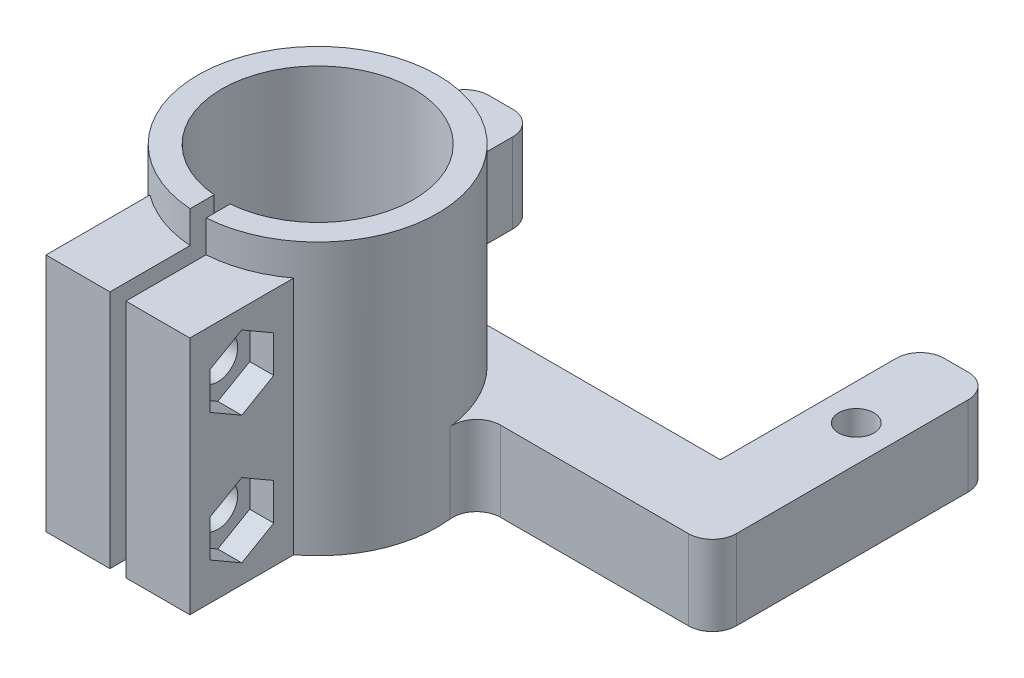
SolidWorks part; units mm, degrees
ref_plane "前视基准面" through (0, 0, 0) normal (0, 0, 1) x (1, 0, 0)
ref_plane "上视基准面" through (0, 0, 0) normal (0, 1, 0) x (1, 0, 0)
ref_plane "右视基准面" through (0, 0, 0) normal (1, 0, 0) x (0, 0, -1)
sketch "草图1" plane through (0, 0, 0) normal (0, 1, 0) x (1, 0, 0)
  circle A0 centre (0, 0) radius 6
  circle A1 centre (0, 0) radius 7.5
  dimension "D1" = 12
  dimension "D2" = 15
extrude "凸台-拉伸1" add sketch "草图1" along normal blind 17
ref_plane "基准面1" through (0, 0, 7.5) normal (0, 0, 1) x (1, 0, 0)
sketch "草图2" plane through (0, 0, 7.5) normal (0, 0, 1) x (1, 0, 0)
  line L0 (0, 0) -> (0, 17) construction
  line L1 (6, 17) -> (-6, 17) construction
  line L2 (-7.5, 0) -> (7.5, 0) construction
  line L3 (-0.5, 17) -> (0.5, 17)
  line L4 (-0.5, 17) -> (-0.5, 0)
  line L5 (-0.5, 0) -> (0.5, 0)
  line L6 (0.5, 17) -> (0.5, 0)
  line L7 (-0.5, 17) -> (0.5, 0) construction
  line L8 (-0.5, 0) -> (0.5, 17) construction
  point P5 (0, 8.5)
  dimension "D1" = 1
extrude "切除-拉伸1" cut sketch "草图2" against normal up to next
sketch "草图3" plane through (0, 0, 7.5) normal (0, 0, 1) x (1, 0, 0)
  line L0 (-7.5, 0) -> (7.5, 0) construction
  line L1 (-0.5, 17) -> (-4.5, 17)
  line L2 (-0.5, 17) -> (-0.5, 0)
  line L3 (-0.5, 0) -> (-4.5, 0)
  line L4 (-4.5, 17) -> (-4.5, 0)
  line L6 (0.5, 17) -> (4.5, 17)
  line L7 (0.5, 17) -> (0.5, 0)
  line L8 (0.5, 0) -> (4.5, 0)
  line L9 (4.5, 17) -> (4.5, 0)
  dimension "D1" = 4
extrude "凸台-拉伸2" add sketch "草图3" along normal blind 5 and the other way up to next
sketch "草图7" plane through (0, 17, 0) normal (0, 1, 0) x (1, 0, 0)
  line L0 (-4.5, -6) -> (-4.5, -12.5)
  line L1 (-4.5, -12.5) -> (4.5, -12.5)
  line L2 (4.5, -12.5) -> (4.5, -6)
  arc A0 (-4.5, -6) -> (4.5, -6) centre (0, 0) ccw
extrude "切除-拉伸4" cut sketch "草图7" against normal blind 2
sketch "草图4" plane through (-4.5, 0, 0) normal (-1, 0, 0) x (0, 0, 1)
  line L0 (6, 7.5) -> (12.5, 7.5) construction
  line L1 (6, 15) -> (6, 0) construction
  line L2 (12.5, 15) -> (12.5, 0) construction
  line L3 (9.25, 11.5) -> (9.25, 3.5) construction
  circle A0 centre (9.25, 11.5) radius 1.25
  circle A1 centre (9.25, 3.5) radius 1.25
  point P9 (9.25, 7.5)
  dimension "D2" = 2.5
  dimension "D1" = 8
extrude "切除-拉伸2" cut sketch "草图4" against normal up to surface (9 mm away) up to face at (4.5, 7.5, 9.25)
sketch "草图5" plane through (4.5, 0, 0) normal (1, 0, 0) x (0, 0, -1)
  line L1 (-9.25, 9.1906) -> (-7.25, 10.3453)
  line L2 (-7.25, 10.3453) -> (-7.25, 12.6547)
  line L3 (-7.25, 12.6547) -> (-9.25, 13.8094)
  line L4 (-9.25, 13.8094) -> (-11.25, 12.6547)
  line L5 (-11.25, 12.6547) -> (-11.25, 10.3453)
  line L6 (-11.25, 10.3453) -> (-9.25, 9.1906)
  line L7 (-9.25, 1.1906) -> (-7.25, 2.3453)
  line L8 (-7.25, 2.3453) -> (-7.25, 4.6547)
  line L9 (-7.25, 4.6547) -> (-9.25, 5.8094)
  line L10 (-9.25, 5.8094) -> (-11.25, 4.6547)
  line L11 (-11.25, 4.6547) -> (-11.25, 2.3453)
  line L12 (-11.25, 2.3453) -> (-9.25, 1.1906)
  circle A0 centre (-9.25, 11.5) radius 2 construction
  circle A1 centre (-9.25, 3.5) radius 2 construction
  dimension "D1" = 4
extrude "切除-拉伸3" cut sketch "草图5" against normal blind 1.5
ref_plane "基准面4" through (0, 0, 0) normal (0, 1, 0) x (1, 0, 0)
sketch "草图12" plane through (0, 0, 0) normal (0, 1, 0) x (1, 0, 0)
  line L0 (-10.8, 7.5) -> (22.2, 7.5)
  line L1 (-10.8, 7.5) -> (-10.8, 2.5)
  line L2 (-10.8, 2.5) -> (-7.0711, 2.5)
  line L3 (-7.0711, 2.5) -> (0, 7.2085)
  line L4 (0, 7.2085) -> (7.0711, 2.5)
  line L5 (7.0711, 2.5) -> (22.2, 2.5)
  line L6 (22.2, 2.5) -> (22.2, 7.5)
  arc A0 (0.5, -7.4833) -> (-0.5, -7.4833) centre (0, 0) ccw construction
  arc A1 (0.5, -5.9791) -> (-0.5, -5.9791) centre (0, 0) ccw construction
  point P13 (5.7, 7.5)
  dimension "D1" = 33
  dimension "D2" = 5
  dimension "D3" = 5.7
extrude "凸台-拉伸6" add sketch "草图12" along normal blind 5
sketch "草图13" plane through (0, 0, 0) normal (0, 1, 0) x (1, 0, 0)
  line L1 (-10.8, 7.5) -> (-6.3, 7.5)
  line L2 (-10.8, 7.5) -> (-10.8, 20)
  line L3 (-10.8, 20) -> (-6.3, 20)
  line L4 (-6.3, 7.5) -> (-6.3, 20)
  line L5 (22.2, 7.5) -> (17.7, 7.5)
  line L6 (22.2, 7.5) -> (22.2, 20)
  line L7 (22.2, 20) -> (17.7, 20)
  line L8 (17.7, 7.5) -> (17.7, 20)
  dimension "D1" = 4.5
  dimension "D2" = 12.5
extrude "凸台-拉伸7" add sketch "草图13" along normal up to surface (5 mm away) up to face at (-7.3664, 5, -5.2809)
sketch "草图11" plane through (0, 5, 0) normal (0, 1, 0) x (1, 0, 0)
  line L0 (-6.3, 20) -> (17.7, 7.5) construction
  line L1 (-8.55, 13.75) -> (19.95, 13.75) construction
  circle A0 centre (-8.55, 13.75) radius 1.1
  circle A1 centre (19.95, 13.75) radius 1.1
  point P5 (5.7, 13.75)
  point P6 (5, 13.75)
  point P11 (7.2492, 13.75)
  dimension "D2" = 2.2
  dimension "D1" = 28.5
extrude "切除-拉伸5" cut sketch "草图11" against normal up to next
fillet "圆角1" radius 1.5 8 edges at (-6.3, 2.5, -20) (-10.8, 2.5, -20) (22.2, 2.5, -20) (17.7, 2.5, -20) (22.2, 2.5, -2.5) (7.0711, 2.5, -2.5) (-7.0711, 2.5, -2.5) (-10.8, 2.5, -2.5)
